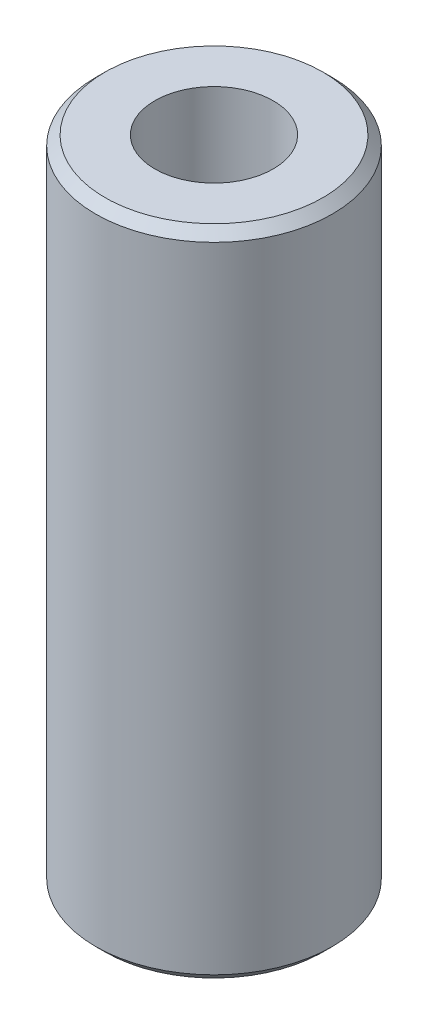
SolidWorks part; units mm, degrees
material "45"
ref_plane "前视基准面" through (0, 0, 0) normal (0, 0, 1) x (1, 0, 0)
ref_plane "上视基准面" through (0, 0, 0) normal (0, 1, 0) x (1, 0, 0)
ref_plane "右视基准面" through (0, 0, 0) normal (1, 0, 0) x (0, 0, -1)
sketch "草图1" plane through (0, 0, 0) normal (0, 1, 0) x (1, 0, 0)
  circle A0 centre (0, 0) radius 2.5
  dimension "D1" = 5
extrude "凸台-拉伸1" add sketch "草图1" along normal mid plane 13.8
hole_wizard "M3 螺纹孔1" positions "草图3" profile "草图2" tap size "M3" standard "Gb"
sketch "草图3" plane through (0, 6.9, 0) normal (0, 1, 0) x (1, 0, 0)
  point P0 (0, 0)
sketch "草图2" plane through (0, 6.9, 0) normal (1, 0, 0) x (0, 0, 1)
  line L0 (0, 0) -> (0, 7.2511)
  line L1 (0, 7.2511) -> (1.25, 6.5)
  line L2 (1.25, 6.5) -> (1.25, 0)
  line L5 (1.25, 0) -> (0, 0)
  line L10 (0, 7.2511) -> (-1.25, 6.5) construction
  line L11 (0, -6.35) -> (0, 107.95) construction
  dimension "螺纹孔钻头直径" = 2.5
  dimension "螺纹孔钻头深度" = 6.5
  dimension "导头角度" = 118
cosmetic thread "孔螺蚊线1" parameters "D1"=4, "D2"=3
hole_wizard "M3 螺纹孔2" positions "草图5" profile "草图4" tap size "M3" standard "Gb"
sketch "草图5" plane through (0, -6.9, 0) normal (0, -1, 0) x (-1, 0, 0)
  point P0 (0, 0)
sketch "草图4" plane through (0, -6.9, 0) normal (1, 0, 0) x (0, 0, -1)
  line L0 (0, 0) -> (0, 7.2511)
  line L1 (0, 7.2511) -> (1.25, 6.5)
  line L2 (1.25, 6.5) -> (1.25, 0)
  line L5 (1.25, 0) -> (0, 0)
  line L10 (0, 7.2511) -> (-1.25, 6.5) construction
  line L11 (0, -6.35) -> (0, 107.95) construction
  dimension "螺纹孔钻头直径" = 2.5
  dimension "螺纹孔钻头深度" = 6.5
  dimension "导头角度" = 118
cosmetic thread "孔螺蚊线2" parameters "D1"=4, "D2"=3
chamfer "倒角1" distance 0.2 angle 45 2 edges at (0, -6.9, 2.5) (0, 6.9, 2.5)
